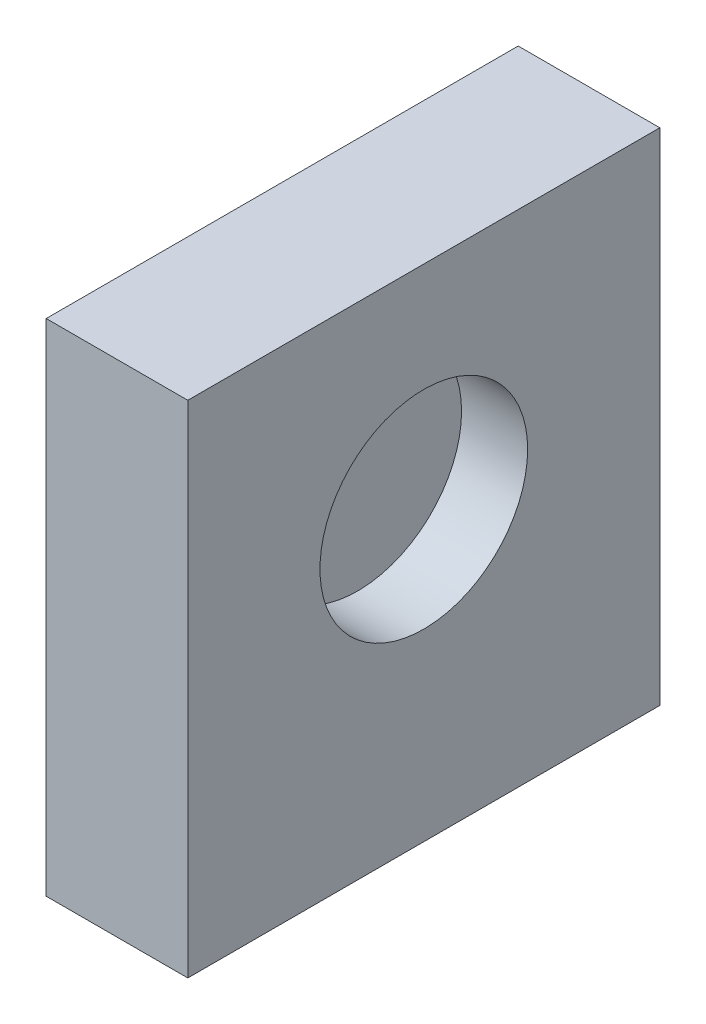
SolidWorks part; units mm, degrees
ref_plane "Alzado" through (0, 0, 0) normal (0, 0, 1) x (1, 0, 0)
ref_plane "Planta" through (0, 0, 0) normal (0, 1, 0) x (1, 0, 0)
ref_plane "Vista lateral" through (0, 0, 0) normal (1, 0, 0) x (0, 0, -1)
sketch "Croquis1" plane through (0, 0, 0) normal (1, 0, 0) x (0, 0, -1)
  line L1 (-25, -26.5) -> (25, -26.5)
  line L2 (-25, -26.5) -> (-25, 26.5)
  line L3 (-25, 26.5) -> (25, 26.5)
  line L4 (25, -26.5) -> (25, 26.5)
  line L5 (-25, -26.5) -> (25, 26.5) construction
  line L6 (-25, 26.5) -> (25, -26.5) construction
  point P0 (0, 0)
  dimension "D1" = 53
  dimension "D2" = 50
extrude "Saliente-Extruir1" add sketch "Croquis1" along normal blind 15
sketch "Croquis2" plane through (15, 0, 0) normal (1, 0, 0) x (0, 0, -1)
  line L0 (-25, -26.5) -> (25, -26.5) construction
  circle A0 centre (0, 4) radius 11
  dimension "D2" = 22
  dimension "D1" = 30.5
extrude "Cortar-Extruir1" cut sketch "Croquis2" against normal blind 7
